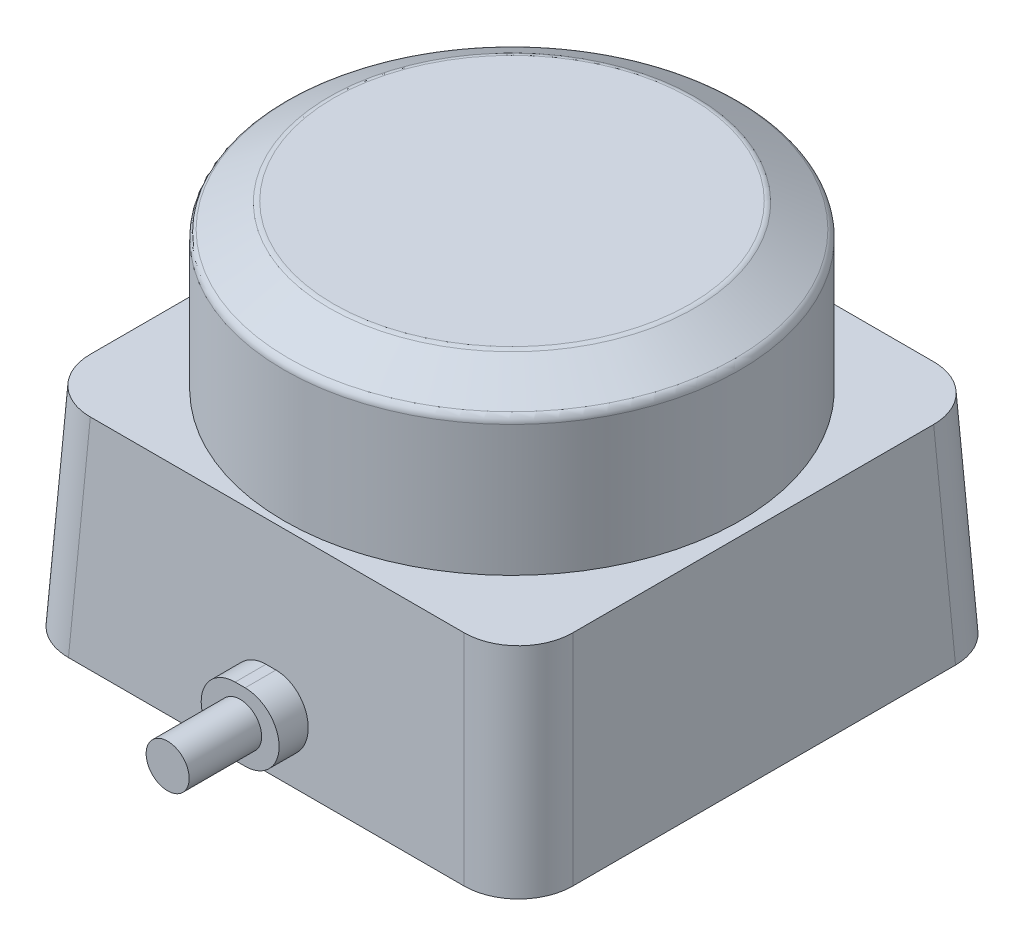
SolidWorks part; units mm, degrees
ref_plane "Front Plane" through (0, 0, 0) normal (0, 0, 1) x (1, 0, 0)
ref_plane "Top Plane" through (0, 0, 0) normal (0, 1, 0) x (1, 0, 0)
ref_plane "Right Plane" through (0, 0, 0) normal (1, 0, 0) x (0, 0, -1)
sketch "Sketch1" plane through (0, 0, 0) normal (0, 1, 0) x (1, 0, 0)
  line L1 (27.825, -27.1103) -> (-27.825, -27.1103)
  line L2 (27.825, -27.1103) -> (27.825, 27.1103)
  line L3 (27.825, 27.1103) -> (-27.825, 27.1103)
  line L4 (-27.825, -27.1103) -> (-27.825, 27.1103)
  line L5 (27.825, -27.1103) -> (-27.825, 27.1103) construction
  line L6 (27.825, 27.1103) -> (-27.825, -27.1103) construction
  point P0 (0, 0)
  dimension "D1" = 55.65
extrude "Boss-Extrude1" add sketch "Sketch1" along normal blind 23 draft 3
sketch "Sketch2" plane through (0, 23, 0) normal (0, 1, 0) x (1, 0, 0)
  circle A0 centre (0, 0) radius 25.15
  dimension "D1" = 50.3
extrude "Boss-Extrude2" add sketch "Sketch2" along normal blind 18
chamfer "Chamfer1" distance 3 angle 60 1 edges at (0, 41, 25.15)
sketch "Sketch3" plane through (0, 0, 0) normal (0, 0, 1) x (1, 0, 0)
  line L0 (0.55, 6) -> (-0.55, 6) construction
  line L1 (0.55, 2.25) -> (-0.55, 2.25)
  line L2 (0.55, 9.75) -> (-0.55, 9.75)
  line L3 (-27.825, 0) -> (27.825, 0) construction
  arc A0 (0.55, 2.25) -> (0.55, 9.75) centre (0.55, 6) ccw
  arc A1 (-0.55, 9.75) -> (-0.55, 2.25) centre (-0.55, 6) ccw
  point P2 (0, 6)
  dimension "D1" = 7.5
  dimension "D2" = 1.1
  dimension "D3" = 6
extrude "Boss-Extrude3" add sketch "Sketch3" along normal blind 30
sketch "Sketch4" plane through (0, 0, 30) normal (0, 0, 1) x (1, 0, 0)
  circle A0 centre (0, 6) radius 2.375
  dimension "D1" = 4.75
extrude "Boss-Extrude4" add sketch "Sketch4" along normal blind 8
sketch "Sketch5" plane through (0, 0, 0) normal (0, -1, 0) x (1, 0, 0)
  line L1 (21.4, -21.4) -> (-21.4, -21.4) construction
  line L2 (21.4, -21.4) -> (21.4, 21.4) construction
  line L3 (21.4, 21.4) -> (-21.4, 21.4) construction
  line L4 (-21.4, -21.4) -> (-21.4, 21.4) construction
  line L5 (21.4, -21.4) -> (-21.4, 21.4) construction
  line L6 (21.4, 21.4) -> (-21.4, -21.4) construction
  circle A0 centre (-21.4, 21.4) radius 1.25
  circle A1 centre (21.4, 21.4) radius 1.25
  circle A2 centre (21.4, -21.4) radius 1.25
  circle A3 centre (-21.4, -21.4) radius 1.25
  point P0 (0, 0)
  dimension "D1" = 2.5
  dimension "D2" = 42.8
extrude "Cut-Extrude1" cut sketch "Sketch5" against normal blind 5
chamfer "Chamfer2" distance 0.2 angle 60 4 edges at (-21.4, 0, 20.15) (21.4, 0, -22.65) (-21.4, 0, -22.65) (21.4, 0, 20.15)
fillet "Fillet1" radius 6 4 edges at (-27.2223, 11.5, 26.5076) (-27.2223, 11.5, -26.5076) (27.2223, 11.5, -26.5076) (27.2223, 11.5, 26.5076)
fillet "Fillet2" radius 1 2 edges at (0, 41, 19.9538) (0, 38, 25.15)
